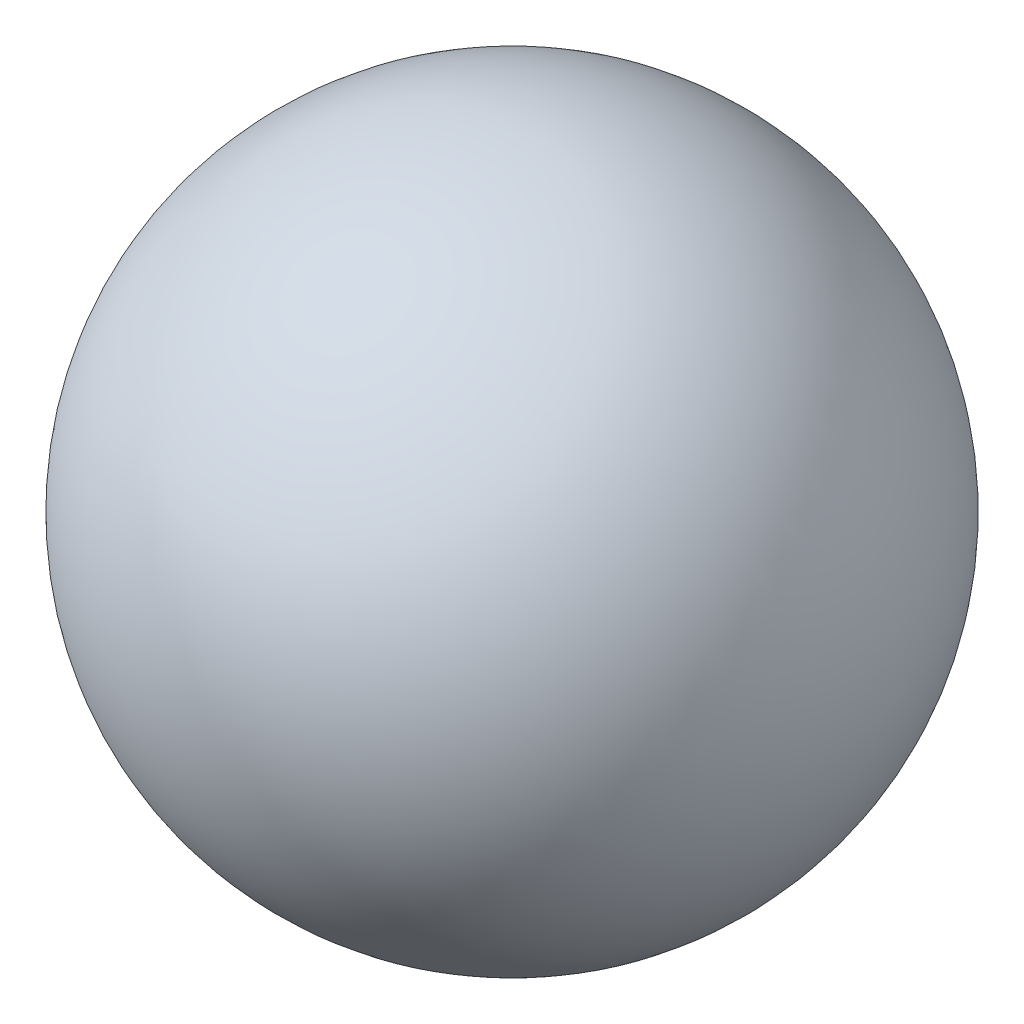
SolidWorks part; units mm, degrees
ref_plane "Front Plane" through (0, 0, 0) normal (0, 0, 1) x (1, 0, 0)
ref_plane "Top Plane" through (0, 0, 0) normal (0, 1, 0) x (1, 0, 0)
ref_plane "Right Plane" through (0, 0, 0) normal (1, 0, 0) x (0, 0, -1)
other "Graphic1"
other "Graphic (Closed) -1"
other "Graphic (Closed) -2"
other "Graphic (Closed) -3"
sketch "Sketch1" plane through (0, 0, 0) normal (0, 0, 1) x (1, 0, 0)
  line L0 (121.2536, 134.7187) -> (121.2536, 94.4725)
  arc A0 (121.2536, 94.4725) -> (121.2536, 134.7187) centre (121.2536, 114.5956) ccw
revolve "Revolve1" add sketch "Sketch1" angle 360 about L0
move or copy body "Body-Move/Copy1" bodies to move or copy 101 copy no translate (0, 0, 22.5449) parameters "D1"=0, "D2"=0, "D3"=22.5449
sketch "Sketch3" plane through (0, 0, 0) normal (0, 0, 1) x (1, 0, 0)
  line L0 (121.2536, 94.4725) -> (121.2536, 164.7414) construction
  line L1 (85.6936, 152.4505) -> (156.8136, 152.4505)
  line L2 (156.8136, 152.4505) -> (156.8136, 86.4105)
  line L3 (156.8136, 86.4105) -> (85.6936, 86.4105)
  line L4 (85.6936, 152.4505) -> (85.6936, 86.4105)
  circle A0 centre (121.2536, 114.5956) radius 20.1231 construction
  point P9 (121.2536, 86.4105)
  point P10 (121.2536, 152.4505)
  dimension "D1" = 66.04
  dimension "D2" = 71.12
sketch "Sketch4" plane through (0, 0, 0) normal (1, 0, 0) x (0, 0, -1)
  line L0 (0, 114.9722) -> (-45.72, 114.9722)
  line L1 (0, 152.4505) -> (0, 86.4105) construction
  dimension "D1" = 45.72
